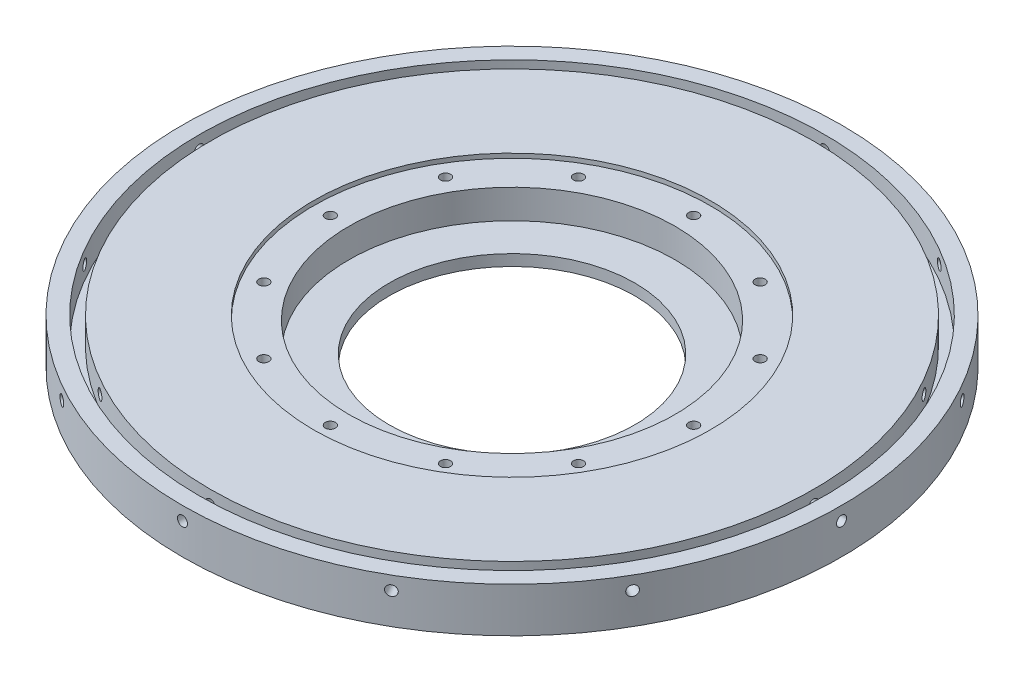
SolidWorks part; units mm, degrees
material "6061-T6 (SS)"
ref_plane "Front Plane" through (0, 0, 0) normal (0, 0, 1) x (1, 0, 0)
ref_plane "Top Plane" through (0, 0, 0) normal (0, 1, 0) x (1, 0, 0)
ref_plane "Right Plane" through (0, 0, 0) normal (1, 0, 0) x (0, 0, -1)
sketch "Sketch1" plane through (0, 0, 0) normal (0, 1, 0) x (1, 0, 0)
  line L5 (0, 0) -> (127.635, 0)
  line L6 (0, 0) -> (0, 127.635)
  line L7 (0, 127.635) -> (127.635, 127.635)
  line L8 (127.635, 0) -> (127.635, 127.635)
  dimension "D1" = 127.635
  dimension "D2" = 127.635
extrude "Boss-Extrude1" add sketch "Sketch1" along normal blind 9.525 contours L5 L8 L7 L6
sketch "Sketch13" plane through (0, 9.525, 0) normal (0, 1, 0) x (1, 0, 0)
  circle A0 centre (63.8175, 63.8175) radius 93.6625
  dimension "D1" = 187.325
extrude "Boss-Extrude2" add sketch "Sketch13" against normal blind 12.7 contours A0
sketch "Sketch6" [suppressed] plane through (127.635, 0, 0) normal (1, 0, 0) x (0, 0, -1)
  circle A0 centre (4.7625, 4.7625) radius 1.3526
  dimension "D1" = 2.7051
extrude "6-32 hole1" [suppressed] cut sketch "Sketch6" against normal blind 12.7
sketch "Sketch7" [suppressed] plane through (0, 0, -127.635) normal (0, 0, -1) x (-1, 0, 0)
  circle A0 centre (-122.8725, 4.7625) radius 1.3525
  dimension "D1" = 2.7051
sketch "Sketch8" [suppressed] plane through (0, 0, 0) normal (-1, 0, 0) x (0, 0, 1)
  circle A0 centre (-122.8725, 4.7625) radius 1.3525
  dimension "D1" = 2.7051
sketch "Sketch9" [suppressed] plane through (0, 0, 0) normal (0, 0, 1) x (1, 0, 0)
  circle A0 centre (4.7625, 4.7625) radius 1.3526
  dimension "D1" = 2.7051
sketch "Sketch5" plane through (0, 9.525, 0) normal (0, 1, 0) x (1, 0, 0)
  circle A0 centre (63.8175, 63.8175) radius 46.355
  circle A1 centre (63.8175, 63.8175) radius 93.6625 construction
  dimension "D1" = 92.71
extrude "Cut-Extrude1" cut sketch "Sketch5" against normal blind 9.525
sketch "Sketch11" plane through (0, 9.525, 0) normal (0, 1, 0) x (1, 0, 0)
  line L0 (63.8175, 63.8175) -> (63.8175, 115.443) construction
  circle A0 centre (63.8175, 115.443) radius 1.4351
  dimension "D2" = 2.8702
  dimension "D1" = 51.6255
extrude "Cut-Extrude3" cut sketch "Sketch11" against normal through all contours A0
pattern_circular "CirPattern1" count 12 over 360 about axis through (63.8175, 0, -63.8175) along (0, 1, 0) of "Cut-Extrude3"
sketch "Sketch12" plane through (0, 9.525, 0) normal (0, 1, 0) x (1, 0, 0)
  circle A0 centre (63.8175, 63.8175) radius 56.4198
  dimension "D1" = 112.8395
extrude "Cut-Extrude4" cut sketch "Sketch12" against normal blind 1.27
sketch "Sketch15" plane through (0, 9.525, 0) normal (0, 1, 0) x (1, 0, 0)
  line L0 (63.8175, 63.8175) -> (-29.845, 63.8175) construction
  line L1 (0, -39.1057) -> (0, 39.1057) construction
  line L2 (-20.0025, 63.8175) -> (-25.0825, 63.8175)
  line L3 (-8.7458, 105.7742) -> (-13.2051, 108.2104)
  line L4 (-8.7458, 105.7742) -> (-20.0025, 63.8175) construction
  circle A0 centre (63.8175, 63.8175) radius 56.4198 construction
  arc A1 (-20.0025, 63.8175) -> (-8.7458, 105.7742) centre (63.8175, 63.8175) cw
  arc A2 (-25.0825, 63.8175) -> (-13.2051, 108.2104) centre (63.8175, 63.8175) cw
  circle A3 centre (63.8175, 63.8175) radius 93.6625 construction
  point P0 (63.8175, 63.8175)
  point P11 (-14.3741, 84.7959)
  dimension "D1" = 46.482
  dimension "D2" = 88.9
  dimension "D3" = 83.82
  dimension "D4" = 43.942
sketch "Sketch16" plane through (0, 9.525, 0) normal (0, 1, 0) x (1, 0, 0)
  circle A0 centre (63.8175, 63.8175) radius 88.9
  circle A1 centre (63.8175, 63.8175) radius 85.725
  dimension "D1" = 177.8
  dimension "D2" = 171.45
extrude "Cut-Extrude5" cut sketch "Sketch16" against normal blind 7.62
sketch "Sketch18" plane through (0, 8.255, 0) normal (0, 1, 0) x (1, 0, 0)
  line L0 (63.8175, 185.7252) -> (63.8175, -48.6103) construction
ref_plane "Plane1" through (63.8175, 0, 0) normal (-1, 0, 0) x (0, 0, 1)
ref_plane "Plane2" through (0, 0, 29.845) normal (0, 0, 1) x (1, 0, 0)
sketch "Sketch17" plane through (0, 0, 29.845) normal (0, 0, 1) x (1, 0, 0)
  line L0 (63.8175, 103.0287) -> (63.8175, -103.0287) construction
  line L1 (157.48, 9.525) -> (-29.845, 9.525) construction
  circle A0 centre (63.8175, 5.715) radius 1.4351
  dimension "D1" = 2.8702
  dimension "D2" = 3.81
extrude "Cut-Extrude6" cut sketch "Sketch17" against normal blind 15.24
pattern_circular "CirPattern2" count 12 over 360 about axis through (63.8175, 0, -63.8175) along (0, 1, 0) of "Cut-Extrude6"
sketch "Sketch19" plane through (0, -3.175, 0) normal (0, -1, 0) x (1, 0, 0)
  circle A0 centre (63.8175, -63.8175) radius 34.925
  dimension "D1" = 69.85
extrude "Cut-Extrude7" cut sketch "Sketch19" against normal blind 87.63
